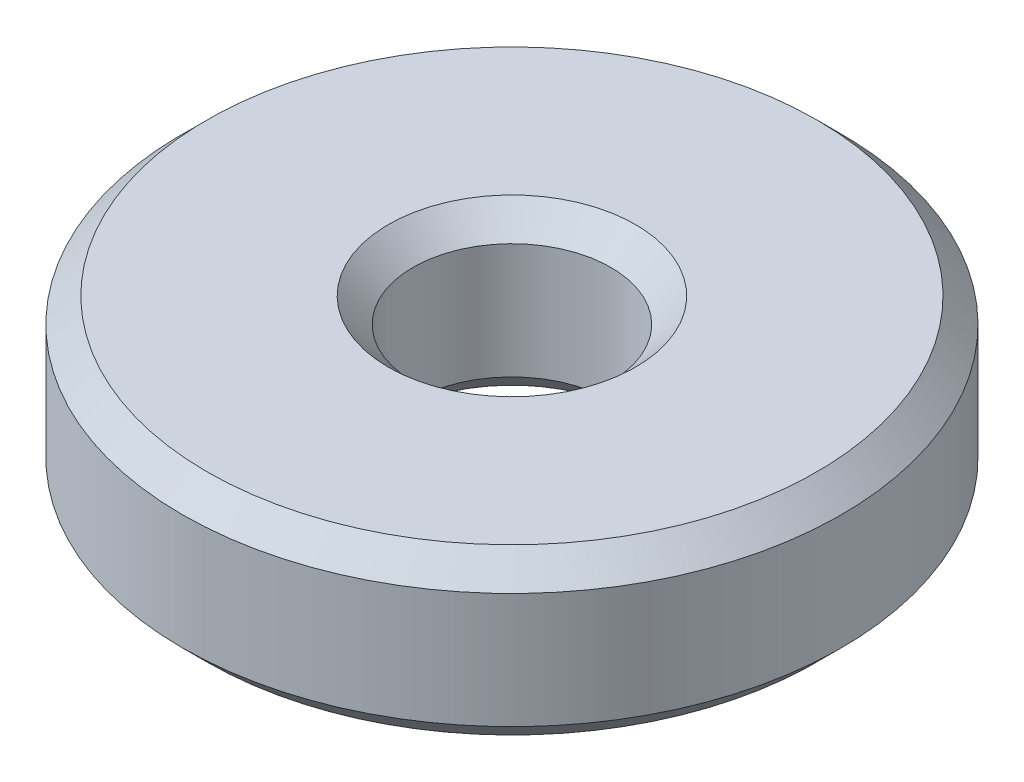
SolidWorks part; units mm, degrees
ref_plane "Front Plane" through (0, 0, 0) normal (0, 0, 1) x (1, 0, 0)
ref_plane "Top Plane" through (0, 0, 0) normal (0, 1, 0) x (1, 0, 0)
ref_plane "Right Plane" through (0, 0, 0) normal (1, 0, 0) x (0, 0, -1)
sketch "Sketch1" plane through (0, 0, 0) normal (0, 1, 0) x (1, 0, 0)
  circle A0 centre (0, 0) radius 10
  circle A1 centre (0, 0) radius 3
  dimension "D1" = 6
  dimension "D2" = 20
extrude "Boss-Extrude1" add sketch "Sketch1" along normal blind 5
chamfer "Chamfer1" distance 0.75 angle 45 4 edges at (0, 0, 3) (0, 5, 3) (0, 0, 10) (0, 5, 10)
